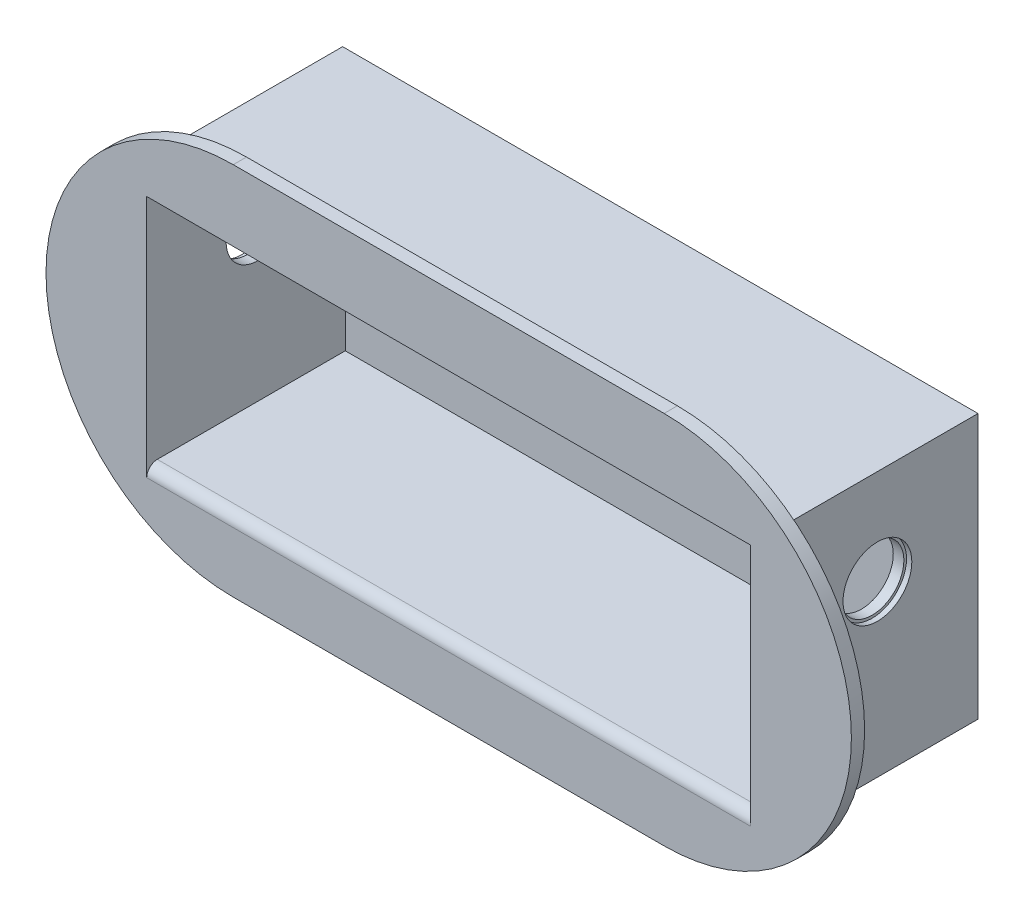
SolidWorks part; units mm, degrees
material "Silicon Rubber"
ref_plane "Front Plane" through (0, 0, 0) normal (0, 0, 1) x (1, 0, 0)
ref_plane "Top Plane" through (0, 0, 0) normal (0, 1, 0) x (1, 0, 0)
ref_plane "Right Plane" through (0, 0, 0) normal (1, 0, 0) x (0, 0, -1)
sketch "Sketch1" plane through (0, 0, 0) normal (0, 0, 1) x (1, 0, 0)
  line L1 (-152.4, 63.5) -> (152.4, 63.5)
  line L2 (-152.4, 63.5) -> (-152.4, -63.5)
  line L3 (-152.4, -63.5) -> (152.4, -63.5)
  line L4 (152.4, 63.5) -> (152.4, -63.5)
  line L5 (-152.4, 63.5) -> (152.4, -63.5) construction
  line L6 (-152.4, -63.5) -> (152.4, 63.5) construction
  point P0 (0, 0)
  dimension "D1" = 304.8
  dimension "D2" = 127
extrude "Boss-Extrude1" add sketch "Sketch1" along normal blind 101.6
sketch3d "3DSketch1"
  line L0 (144.78, 55.88, 101.6) -> (-144.78, 55.88, 101.6)
  line L1 (-144.78, 55.88, 101.6) -> (-144.78, -55.88, 101.6)
  line L2 (-144.78, -55.88, 101.6) -> (144.78, -55.88, 101.6)
  line L3 (144.78, -55.88, 101.6) -> (144.78, 55.88, 101.6)
  line L4 (144.78, 55.88, 101.6) -> (-144.78, 55.88, 101.6)
  line L5 (-144.78, 55.88, 101.6) -> (-144.78, -55.88, 101.6)
  line L6 (-144.78, -55.88, 101.6) -> (144.78, -55.88, 101.6)
  line L7 (144.78, -55.88, 101.6) -> (144.78, 55.88, 101.6)
  dimension "D1" = 7.62
extrude "Cut-Extrude2" cut sketch "3DSketch1" along direction (0, 0, 1) on the side against the normal blind 95.25
sketch "Sketch3" plane through (0, 0, 101.6) normal (0, 0, 1) x (1, 0, 0)
  line L0 (-103.2595, 0) -> (103.425, 0) construction
  line L1 (-103.2595, 89.8371) -> (103.425, 89.8371)
  line L2 (-103.2595, -89.8371) -> (103.425, -89.8371)
  line L5 (-152.4, 63.5) -> (-152.4, -63.5) construction
  line L8 (-144.78, 55.88) -> (144.78, 55.88)
  line L9 (-144.78, 55.88) -> (-144.78, -55.88)
  line L10 (-144.78, -55.88) -> (144.78, -55.88)
  line L11 (144.78, 55.88) -> (144.78, -55.88)
  line L12 (-144.78, 55.88) -> (144.78, -55.88) construction
  line L13 (-144.78, -55.88) -> (144.78, 55.88) construction
  arc A0 (-103.2595, 89.8371) -> (-103.2595, -89.8371) centre (-103.2595, 0) ccw
  arc A1 (103.425, -89.8371) -> (103.425, 89.8371) centre (103.425, 0) ccw
  point P2 (0.0828, 0)
  point P11 (0, 0)
  dimension "D1" = 89.8371
  dimension "D2" = 49.1405
  dimension "D3" = 152.4828
extrude "Boss-Extrude2" add sketch "Sketch3" against normal blind 6.35
sketch "Sketch5" plane through (-152.4, 0, 0) normal (-1, 0, 0) x (0, 0, 1)
  line L0 (95.25, 63.5) -> (0, 63.5) construction
  line L2 (101.6, -89.8371) -> (101.6, 89.8371) construction
  circle A0 centre (48.26, 17.78) radius 15.24
  dimension "D1" = 30.48
  dimension "D2" = 45.72
  dimension "D3" = 53.34
extrude "Cut-Extrude4" cut sketch "Sketch5" against normal through all
fillet "Fillet2" radius 5.08 1 edges
sketch "Sketch6" plane through (152.4, 0, 0) normal (1, 0, 0) x (0, 0, -1)
  circle A0 centre (-48.26, 17.78) radius 16.51
  dimension "D1" = 33.02
extrude "Cut-Extrude5" cut sketch "Sketch6" against normal blind 2.54
mirror "Mirror1" about plane through (0, 0, 0) normal (1, 0, 0) of "Cut-Extrude5"
